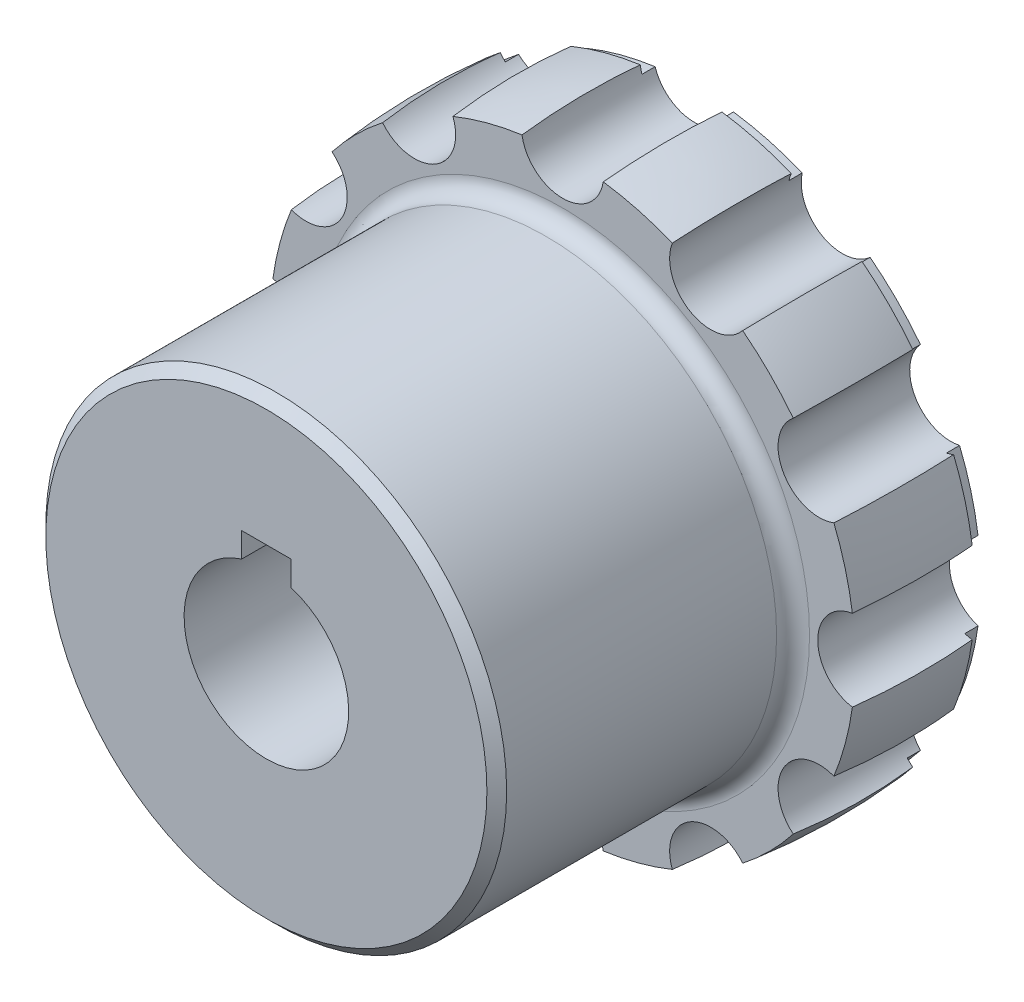
SolidWorks part; units mm, degrees
ref_plane "前视" through (0, 0, 0) normal (0, 0, 1) x (1, 0, 0)
ref_plane "上视" through (0, 0, 0) normal (0, 1, 0) x (1, 0, 0)
ref_plane "右视" through (0, 0, 0) normal (1, 0, 0) x (0, 0, -1)
sketch "草图1" plane through (0, 0, 0) normal (0, 0, 1) x (1, 0, 0)
  circle A0 centre (0, 0) radius 130
  dimension "D1" = 260
extrude "凸台-拉伸1" add sketch "草图1" along normal blind 40
sketch "草图2" plane through (0, 0, 0) normal (0, 0, 1) x (1, 0, 0)
  circle A0 centre (0, 0) radius 70
  dimension "D1" = 140
extrude "凸台-拉伸2" add sketch "草图2" along normal blind 130
sketch "草图3" plane through (0, 0, 0) normal (0, 1, 0) x (1, 0, 0)
  line L0 (0, 59.3731) -> (0, -282.5672) construction
  line L1 (130, -20) -> (-98.4903, -20) construction
  line L2 (130, -40) -> (130, 0) construction
  line L3 (-87, 0) -> (-87, -4)
  line L4 (130, 0) -> (-130, 0) construction
  line L5 (-87, -4) -> (-89.2875, -4)
  line L6 (-88.8854, -40) -> (0, -40) construction
  line L7 (-130, -40) -> (130, -40) construction
  line L8 (0, -40) -> (0, 0) construction
  line L9 (0, 0) -> (-87, 0) construction
  line L10 (-87, 0) -> (-140, 0)
  line L11 (-140, 0) -> (-140, -40)
  line L12 (-140, -40) -> (-88.8854, -40)
  line L13 (-130, 0) -> (-130, -40) construction
  line L14 (-90, -20) -> (-90, 22.025) construction
  arc A0 (-89.2875, -4) -> (-88.8854, -40) centre (90, -20) ccw
  dimension "D1" = 360
  dimension "D3" = 3
  dimension "D2" = 90
  dimension "D4" = 4
  dimension "D5" = 10
revolve "切除-旋转1" cut sketch "草图3" angle 360 about L0
sketch "草图4" plane through (0, 0, 40) normal (0, 0, 1) x (1, 0, 0)
  circle A0 centre (0, 0) radius 90 construction
  circle A1 centre (0, 90) radius 12.5
  circle A2 centre (45, 77.9423) radius 12.5
  circle A3 centre (77.9423, 45) radius 12.5
  circle A4 centre (90, 0) radius 12.5
  circle A5 centre (77.9423, -45) radius 12.5
  circle A6 centre (45, -77.9423) radius 12.5
  circle A7 centre (0, -90) radius 12.5
  circle A8 centre (-45, -77.9423) radius 12.5
  circle A9 centre (-77.9423, -45) radius 12.5
  circle A10 centre (-90, 0) radius 12.5
  circle A11 centre (-77.9423, 45) radius 12.5
  circle A12 centre (-45, 77.9423) radius 12.5
  dimension "D1" = 180
  dimension "D2" = 25
  dimension "D3" = 12
extrude "切除-拉伸1" cut sketch "草图4" against normal blind 70
fillet "圆角1" radius 5 1 edges at (70, 0, 40)
chamfer "倒角1" distance 3 angle 45 1 edges at (70, 0, 130)
scale "缩放比例1" scale about centroid uniform scaling yes scale factor 0.2
sketch "草图8" plane through (0, 0, 73.5086) normal (0, 0, 1) x (1, 0, 0)
  line L1 (1.5, 4.7697) -> (1.5, 6.2697)
  line L3 (-1.5, 4.7697) -> (-1.5, 6.2697)
  line L4 (1.5, 6.2697) -> (-1.5, 6.2697)
  arc A1 (-1.5, 4.7697) -> (1.5, 4.7697) centre (0, 0) ccw
  dimension "D1" = 5
  dimension "D2" = 3
  dimension "D3" = 1.5
  dimension "D4" = 1.5
extrude "切除-拉伸3" cut sketch "草图8" against normal through all
